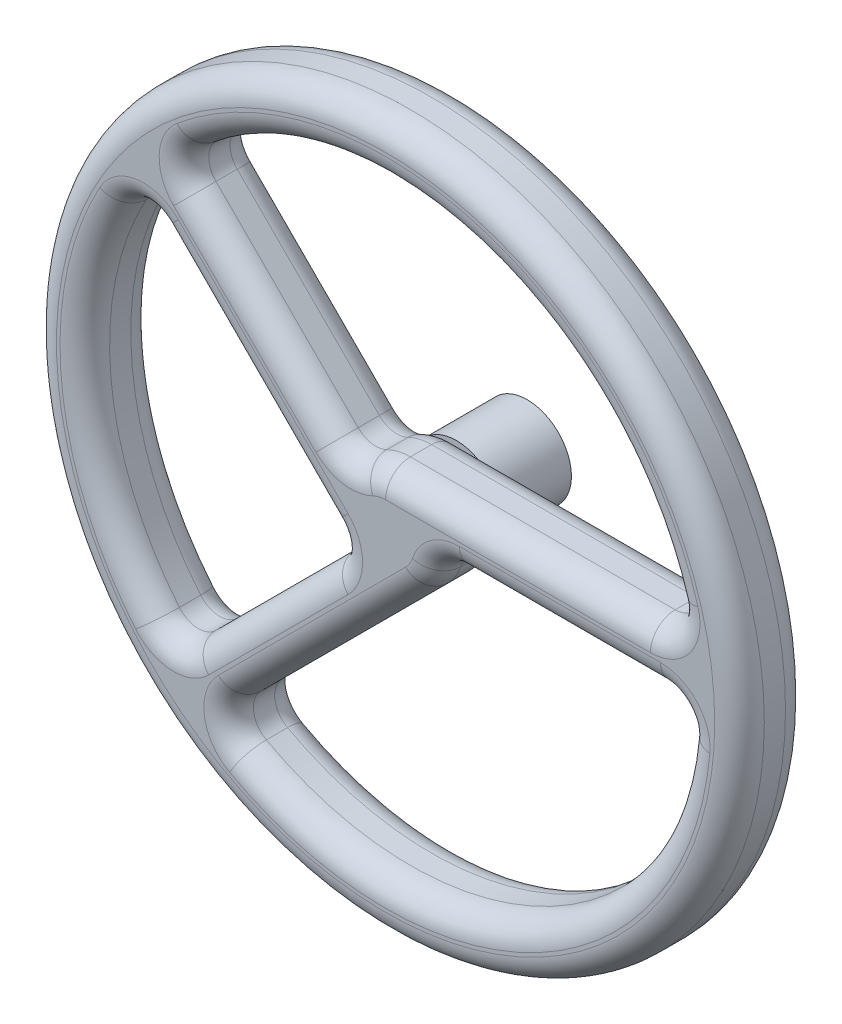
SolidWorks part; units mm, degrees
ref_plane "Front Plane" through (0, 0, 0) normal (0, 0, 1) x (1, 0, 0)
ref_plane "Top Plane" through (0, 0, 0) normal (0, 1, 0) x (1, 0, 0)
ref_plane "Right Plane" through (0, 0, 0) normal (1, 0, 0) x (0, 0, -1)
sketch "Sketch1" plane through (0, 0, 0) normal (0, 0, 1) x (1, 0, 0)
  line L0 (0, 15) -> (0, 40.0995) construction
  line L1 (-10.6066, -10.6066) -> (-23.7363, -23.7363) construction
  line L2 (10.6066, -10.6066) -> (21.7627, -21.7627) construction
  line L4 (-10.6066, -10.6066) -> (-60.1041, -60.1041)
  line L5 (10.6066, -10.6066) -> (-48.5542, -69.7674)
  line L8 (-10.6066, -10.6066) -> (-69.7674, 48.5542)
  line L9 (-10.6066, 10.6066) -> (-60.1041, 60.1041)
  line L12 (0, 15) -> (83.666, 15)
  line L13 (15, 0) -> (85, 0)
  circle A0 centre (0, 0) radius 100
  arc A1 (-48.5542, -69.7674) -> (85, 0) centre (0, 0) ccw
  circle A2 centre (0, 0) radius 15
  arc A3 (-69.7674, 48.5542) -> (-60.1041, -60.1041) centre (0, 0) ccw
  arc A4 (83.666, 15) -> (-60.1041, 60.1041) centre (0, 0) ccw
  point P4 (-10.6066, -10.6066)
  point P8 (0, 0)
  point P9 (10.6066, -10.6066)
  point P10 (0, 15)
  dimension "D1" = 200
  dimension "D2" = 170
  dimension "D3" = 135
  dimension "D4" = 135
  dimension "D5" = 15
  dimension "D6" = 15
  dimension "D7" = 15
extrude "Boss-Extrude1" add sketch "Sketch1" along normal blind 20 contours A0 A4 L12 A2 L13 A1 L5 L4 A3 L8 L9 | A2
fillet "Fillet17" radius 7 33 edges at (-10.6066, -10.6066, 10) (-60.1041, -60.1041, 10) (-69.7674, 48.5542, 10) (15, 0, 10) (85, 0, 10) (-48.5542, -69.7674, 10) (-10.6066, 10.6066, 10) (-60.1041, 60.1041, 10) (83.666, 15, 10) (100, 0, 20) (-84.6658, -7.5296, 20) (-35.3553, -35.3553, 20) (-40.187, 18.9738, 20) (39.3567, -75.3396, 20) (50, 0, 20) (13.8582, -5.7403, 20) (-18.9738, -40.187, 20) (25.4438, 81.1025, 20) (-35.3553, 35.3553, 20) (-5.7403, 13.8582, 20) (41.833, 15, 20) (-84.6658, -7.5296, 0) (-35.3553, -35.3553, 0) (-40.187, 18.9738, 0) (39.3567, -75.3396, 0) (50, 0, 0) (13.8582, -5.7403, 0) (-18.9738, -40.187, 0) (25.4438, 81.1025, 0) (-35.3553, 35.3553, 0) (-5.7403, 13.8582, 0) (41.833, 15, 0) (100, 0, 0)
sketch "Sketch2" plane through (0, 0, 0) normal (0, 0, -1) x (-1, 0, 0)
  circle A1 centre (0, 0) radius 12.5
  dimension "D1" = 25
extrude "Boss-Extrude2" add sketch "Sketch2" along normal blind 20
